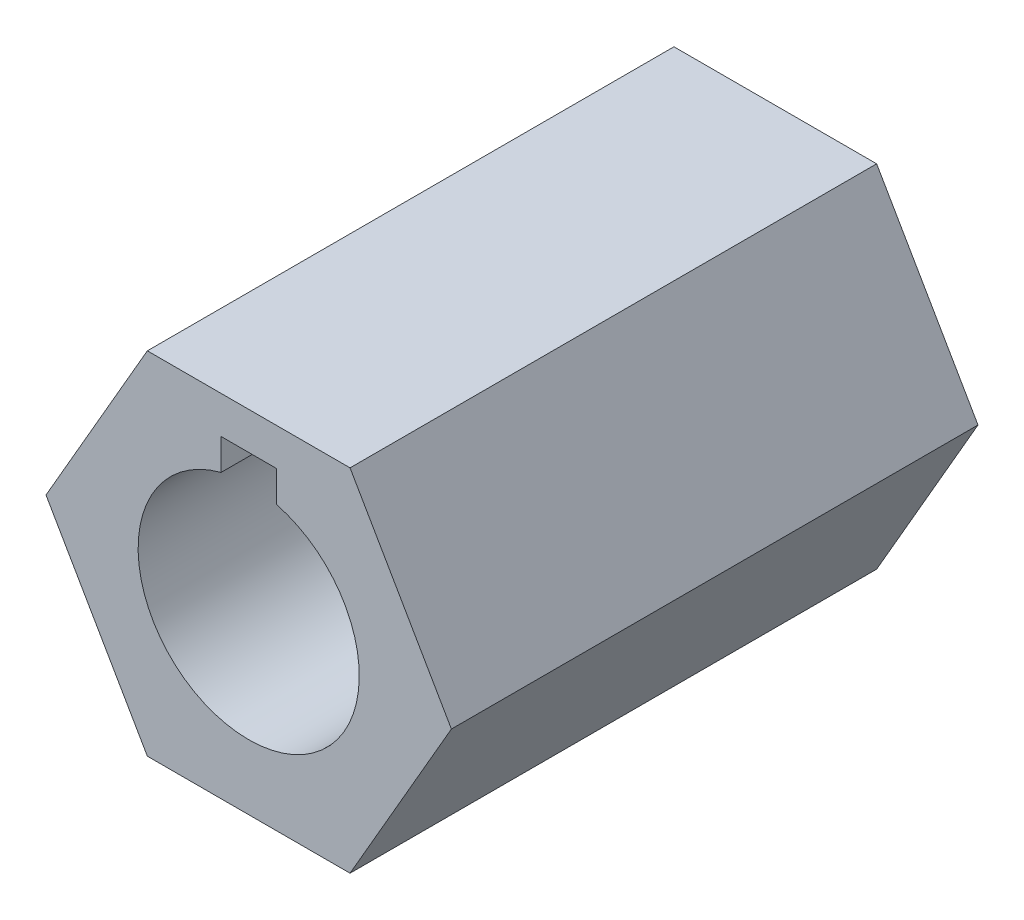
SolidWorks part; units mm, degrees
material "6061 Alloy"
ref_plane "Front Plane" through (0, 0, 0) normal (0, 0, 1) x (1, 0, 0)
ref_plane "Top Plane" through (0, 0, 0) normal (0, 1, 0) x (1, 0, 0)
ref_plane "Right Plane" through (0, 0, 0) normal (1, 0, 0) x (0, 0, -1)
sketch "Sketch1" plane through (0, 0, 0) normal (0, 0, 1) x (1, 0, 0)
  line L1 (7.3323, 0) -> (3.6662, 6.35)
  line L2 (3.6662, 6.35) -> (-3.6662, 6.35)
  line L3 (-3.6662, 6.35) -> (-7.3323, 0)
  line L4 (-7.3323, 0) -> (-3.6662, -6.35)
  line L5 (-3.6662, -6.35) -> (3.6662, -6.35)
  line L6 (3.6662, -6.35) -> (7.3323, 0)
  line L7 (1, 3) -> (-1, 3)
  line L8 (1, 3) -> (1, 5)
  line L9 (1, 5) -> (-1, 5)
  line L10 (-1, 3) -> (-1, 5)
  line L11 (1, 3) -> (-1, 5) construction
  line L12 (1, 5) -> (-1, 3) construction
  circle A0 centre (0, 0) radius 6.35 construction
  circle A1 centre (0, 0) radius 4
  point P10 (0, 4)
  dimension "D1" = 12.7
  dimension "D2" = 8
  dimension "D3" = 2
  dimension "D4" = 2
extrude "Boss-Extrude1" add sketch "Sketch1" along normal blind 19.05 contours L5 L6 L1 L2 L3 L4 A1 L10 L9 L8
